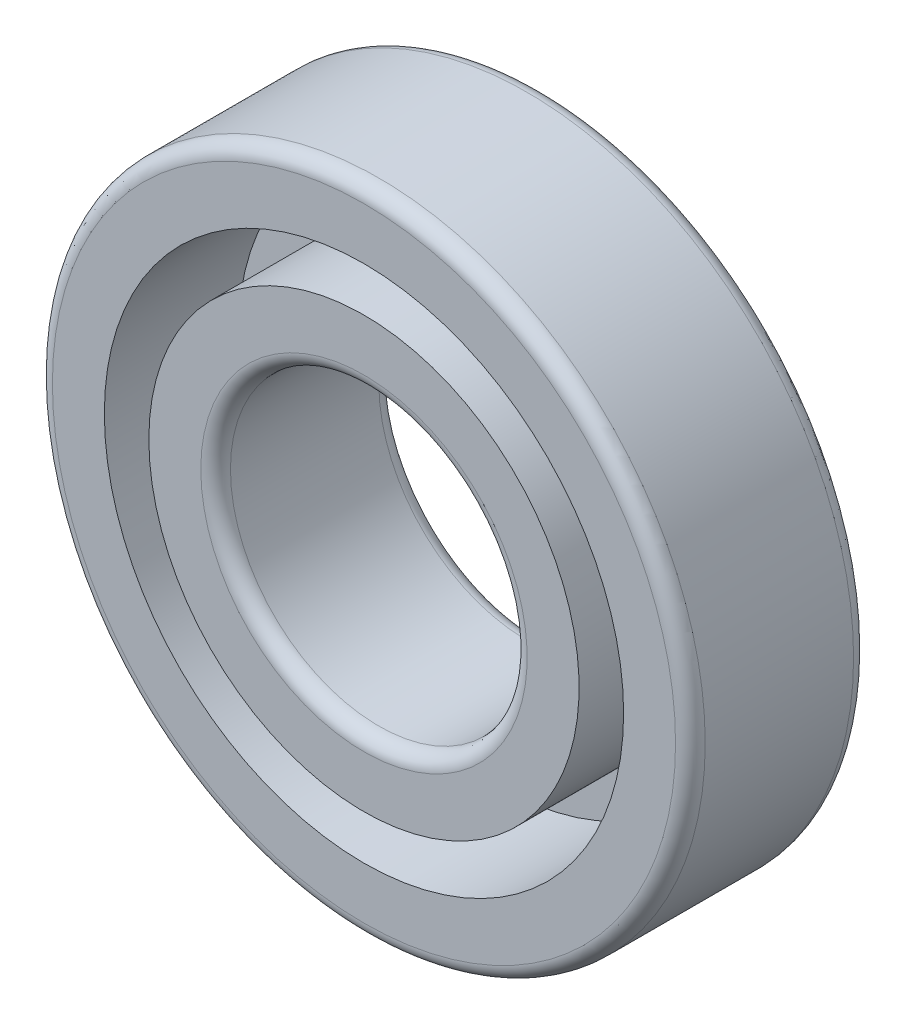
SolidWorks part; units mm, degrees
ref_plane "Front Plane" through (0, 0, 0) normal (0, 0, 1) x (1, 0, 0)
ref_plane "Top Plane" through (0, 0, 0) normal (0, 1, 0) x (1, 0, 0)
ref_plane "Right Plane" through (0, 0, 0) normal (1, 0, 0) x (0, 0, -1)
ref_plane "Plane1" through (0, 22, 0) normal (0, -1, 0) x (1, 0, 0)
sketch "Sketch1" plane through (0, 22, 0) normal (0, -1, 0) x (1, 0, 0)
  line L0 (5, 2.5) -> (5, -2.5)
  line L1 (5.5, -3) -> (10.5, -3)
  line L2 (11, -2.5) -> (11, 2.5)
  line L3 (10.5, 3) -> (8.75, 3)
  line L4 (8.75, 3) -> (8.75, -1.5)
  line L5 (8.75, -1.5) -> (7.25, -1.5)
  line L6 (7.25, -1.5) -> (7.25, 3)
  line L7 (7.25, 3) -> (5.5, 3)
  line L8 (0, 3) -> (0, -3) construction
  arc A0 (5, -2.5) -> (5.5, -3) centre (5.5, -2.5) ccw
  arc A1 (10.5, -3) -> (11, -2.5) centre (10.5, -2.5) ccw
  arc A2 (11, 2.5) -> (10.5, 3) centre (10.5, 2.5) ccw
  arc A3 (5.5, 3) -> (5, 2.5) centre (5.5, 2.5) ccw
  point P14 (5, 0)
  point P15 (11, 0)
  point P17 (0, 0)
  point P18 (8, -1.5)
  point P19 (8, -3)
  dimension "D4" = 0.5
  dimension "D1" = 6
  dimension "D2" = 11
  dimension "D3" = 5
  dimension "D5" = 4.5
  dimension "D6" = 1.5
revolve "Revolve1" add sketch "Sketch1" angle 360 about L8
